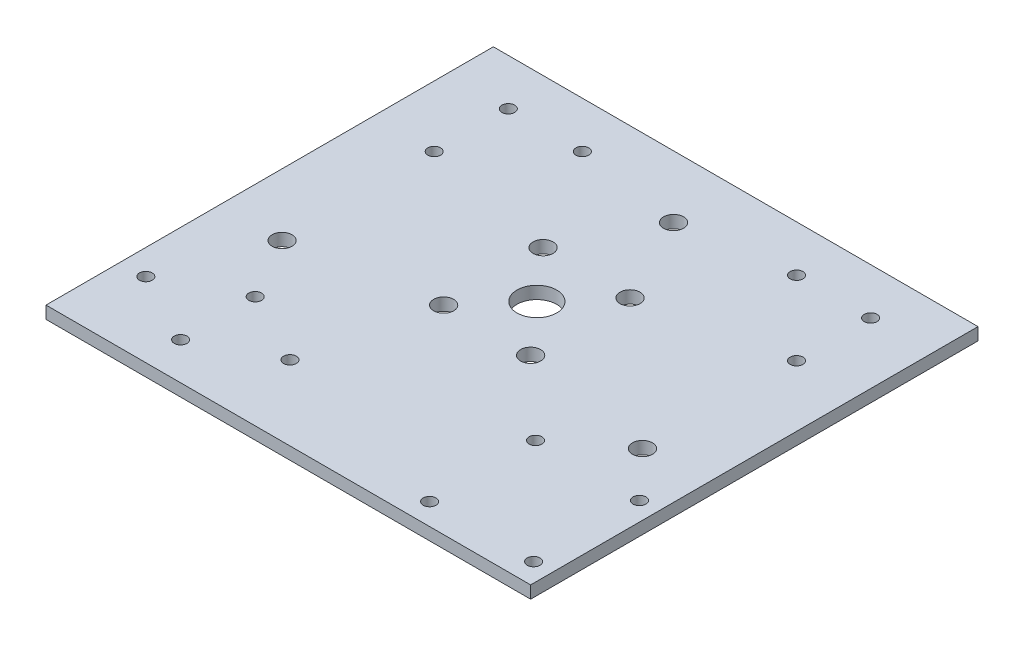
SolidWorks part; units mm, degrees
material "6061 Alloy"
ref_plane "Front Plane" through (0, 0, 0) normal (0, 0, 1) x (1, 0, 0)
ref_plane "Top Plane" through (0, 0, 0) normal (0, 1, 0) x (1, 0, 0)
ref_plane "Right Plane" through (0, 0, 0) normal (1, 0, 0) x (0, 0, -1)
sketch "Sketch1" plane through (0, 0, 0) normal (0, 1, 0) x (1, 0, 0)
  line L1 (-61.9125, -57.15) -> (61.9125, -57.15)
  line L2 (-61.9125, -57.15) -> (-61.9125, 57.15)
  line L3 (-61.9125, 57.15) -> (61.9125, 57.15)
  line L4 (61.9125, -57.15) -> (61.9125, 57.15)
  line L5 (-61.9125, -57.15) -> (61.9125, 57.15) construction
  line L6 (-61.9125, 57.15) -> (61.9125, -57.15) construction
  point P0 (0, 0)
  dimension "D1" = 114.3
  dimension "D2" = 123.825
extrude "Plate" add sketch "Sketch1" along normal blind 3.175 contours L1 L4 L3 L2
sketch "Sketch2" plane through (0, 3.175, 0) normal (0, 1, 0) x (1, 0, 0)
  circle A0 centre (0, 6.35) radius 5.08
  dimension "D1" = 10.16
  dimension "D2" = 6.35
extrude "Force Sensor Post Hole" cut sketch "Sketch2" against normal through all
hole_wizard "Gearbox Mount Holes (#4 clearance)" positions "Sketch9" profile "Sketch8" hole size "#4" standard "ANSI Inch" end condition up to next
sketch "Sketch9" plane through (0, 3.175, 0) normal (0, 1, 0) x (1, 0, 0)
  line L1 (-18.6309, -28.575) -> (-55.4609, -28.575) construction
  line L2 (-18.6309, -28.575) -> (-18.6309, -47.625) construction
  line L3 (-18.6309, -47.625) -> (-55.4609, -47.625) construction
  line L4 (-55.4609, -28.575) -> (-55.4609, -47.625) construction
  line L5 (-18.6309, -28.575) -> (-55.4609, -47.625) construction
  line L6 (-18.6309, -47.625) -> (-55.4609, -28.575) construction
  line L7 (-61.9125, -57.15) -> (-61.9125, 57.15) construction
  line L8 (-61.9125, -57.15) -> (61.9125, -57.15) construction
  point P0 (-55.4609, -38.1)
  point P3 (-37.0459, -28.575)
  point P6 (-18.6309, -38.1)
  point P9 (-37.0459, -47.625)
  dimension "D1" = 36.83
  dimension "D2" = 19.05
  dimension "D3" = 6.4516
  dimension "D4" = 9.525
sketch "Sketch8" plane through (-55.4609, 3.175, 38.1) normal (1, 0, 0) x (0, 0, 1)
  line L0 (0, 0) -> (0, 3.175)
  line L1 (0, 3.175) -> (1.6319, 3.175)
  line L2 (1.6319, 3.175) -> (1.6319, 0)
  line L5 (1.6319, 0) -> (0, 0)
  line L11 (0, -6.35) -> (0, 107.95) construction
  dimension "Thru Hole Dia." = 3.2639
  dimension "Thru Hole Depth" = 3.175
hole_wizard "Bearing Mount Holes (#4 clearance)" positions "Sketch12" profile "Sketch11" hole size "#4" standard "ANSI Inch"
sketch "Sketch12" plane through (0, 3.175, 0) normal (0, 1, 0) x (1, 0, 0)
  line L1 (30.5816, -51.6255) -> (57.15, -51.6255) construction
  line L2 (30.5816, -51.6255) -> (30.5816, -24.5745) construction
  line L3 (30.5816, -24.5745) -> (57.15, -24.5745) construction
  line L4 (57.15, -51.6255) -> (57.15, -24.5745) construction
  line L5 (30.5816, -51.6255) -> (57.15, -24.5745) construction
  line L6 (30.5816, -24.5745) -> (57.15, -51.6255) construction
  line L8 (-18.6309, -38.1) -> (30.5816, -38.1) construction
  point P3 (57.15, -24.5745)
  point P6 (30.5816, -51.6255)
  point P54 (30.5816, -24.5745)
  point P55 (57.15, -51.6255)
  dimension "D1" = 26.5684
  dimension "D2" = 27.051
  dimension "D3" = 49.2125
sketch "Sketch11" plane through (57.15, 3.175, 24.5745) normal (1, 0, 0) x (0, 0, 1)
  line L0 (0, 0) -> (0, 8.6006)
  line L1 (0, 8.6006) -> (1.6319, 7.62)
  line L2 (1.6319, 7.62) -> (1.6319, 0)
  line L5 (1.6319, 0) -> (0, 0)
  line L10 (0, 8.6006) -> (-1.632, 7.62) construction
  line L11 (0, -6.35) -> (0, 107.95) construction
  dimension "Hole Dia." = 3.2639
  dimension "Hole Depth" = 7.62
  dimension "Drill Angle" = 118
hole_wizard "Force Sensor Foundation Holes (#10 clearance)" positions "Sketch17" profile "Sketch16" hole size "#10" standard "ANSI Inch"
sketch "Sketch17" plane through (0, 3.175, 0) normal (0, 1, 0) x (1, 0, 0)
  line L1 (-11.1125, -6.35) -> (11.1125, -6.35) construction
  line L2 (-11.1125, -6.35) -> (-11.1125, 19.05) construction
  line L3 (-11.1125, 19.05) -> (11.1125, 19.05) construction
  line L4 (11.1125, -6.35) -> (11.1125, 19.05) construction
  line L5 (-11.1125, -6.35) -> (11.1125, 19.05) construction
  line L6 (-11.1125, 19.05) -> (11.1125, -6.35) construction
  point P24 (-11.1125, -6.35)
  point P25 (11.1125, 19.05)
  point P72 (-11.1125, 19.05)
  point P73 (11.1125, -6.35)
  point P81 (0, 6.35)
  dimension "D1" = 22.225
  dimension "D2" = 25.4
sketch "Sketch16" plane through (-11.1125, 3.175, 6.35) normal (1, 0, 0) x (0, 0, 1)
  line L0 (0, 0) -> (0, 9.1538)
  line L1 (0, 9.1538) -> (2.5527, 7.62)
  line L2 (2.5527, 7.62) -> (2.5527, 0)
  line L5 (2.5527, 0) -> (0, 0)
  line L10 (0, 9.1538) -> (-2.5527, 7.62) construction
  line L11 (0, -6.35) -> (0, 107.95) construction
  dimension "Hole Dia." = 5.1054
  dimension "Hole Depth" = 7.62
  dimension "Drill Angle" = 118
hole_wizard "Ball Caster Mount Holes (#4 clearance)" positions "Sketch19" profile "Sketch18" hole size "#4" standard "ANSI Inch" end condition up to next
sketch "Sketch19" plane through (0, 3.175, 0) normal (0, 1, 0) x (1, 0, 0)
  line L1 (-61.9125, 57.15) -> (-30.6705, 57.15) construction
  line L2 (-61.9125, 57.15) -> (-61.9125, 33.528) construction
  line L3 (-61.9125, 33.528) -> (-30.6705, 33.528) construction
  line L4 (-30.6705, 57.15) -> (-30.6705, 33.528) construction
  line L5 (-61.9125, 57.15) -> (-30.6705, 33.528) construction
  line L6 (-61.9125, 33.528) -> (-30.6705, 57.15) construction
  line L8 (-46.2915, 45.339) -> (-27.3685, 45.339) construction
  line L9 (-46.2915, 45.339) -> (-46.2915, 26.416) construction
  line L10 (-46.2915, 26.416) -> (-27.3685, 26.416) construction
  line L11 (-27.3685, 45.339) -> (-27.3685, 26.416) construction
  line L12 (-46.2915, 45.339) -> (-27.3685, 26.416) construction
  line L13 (-46.2915, 26.416) -> (-27.3685, 45.339) construction
  line L15 (61.9125, 57.15) -> (30.6705, 57.15) construction
  line L16 (61.9125, 57.15) -> (61.9125, 33.528) construction
  line L17 (61.9125, 33.528) -> (30.6705, 33.528) construction
  line L18 (30.6705, 57.15) -> (30.6705, 33.528) construction
  line L19 (61.9125, 57.15) -> (30.6705, 33.528) construction
  line L20 (61.9125, 33.528) -> (30.6705, 57.15) construction
  line L22 (46.2915, 45.339) -> (27.3685, 45.339) construction
  line L23 (46.2915, 45.339) -> (46.2915, 26.416) construction
  line L24 (46.2915, 26.416) -> (27.3685, 26.416) construction
  line L25 (27.3685, 45.339) -> (27.3685, 26.416) construction
  line L26 (46.2915, 45.339) -> (27.3685, 26.416) construction
  line L27 (46.2915, 26.416) -> (27.3685, 45.339) construction
  point P129 (-46.2915, 45.339)
  point P181 (-46.2915, 26.416)
  point P182 (-27.3685, 45.339)
  point P287 (46.2915, 45.339)
  point P377 (46.2915, 26.416)
  point P378 (27.3685, 45.339)
  dimension "D1" = 31.242
  dimension "D2" = 23.622
  dimension "D3" = 18.923
sketch "Sketch18" plane through (-46.2915, 3.175, -45.339) normal (1, 0, 0) x (0, 0, 1)
  line L0 (0, 0) -> (0, 3.175)
  line L1 (0, 3.175) -> (1.6319, 3.175)
  line L2 (1.6319, 3.175) -> (1.6319, 0)
  line L5 (1.6319, 0) -> (0, 0)
  line L11 (0, -6.35) -> (0, 107.95) construction
  dimension "Thru Hole Dia." = 3.2639
  dimension "Thru Hole Depth" = 3.175
hole_wizard "Top Plate Guide Holes (#10 clearance)" positions "Sketch21" profile "Sketch20" hole size "#10" standard "ANSI Inch" end condition up to next
sketch "Sketch21" plane through (0, 3.175, 0) normal (0, 1, 0) x (1, 0, 0)
  line L0 (-61.9125, 57.15) -> (61.9125, 57.15) construction
  line L1 (-61.9125, -57.15) -> (-61.9125, 57.15) construction
  line L2 (-61.9125, -57.15) -> (61.9125, -57.15) construction
  line L3 (61.9125, -57.15) -> (61.9125, 57.15) construction
  point P0 (-46.0375, -12.7)
  point P2 (46.0375, -12.7)
  point P4 (0, 41.275)
  dimension "D1" = 15.875
  dimension "D2" = 15.875
  dimension "D3" = 44.45
  dimension "D4" = 15.875
sketch "Sketch20" plane through (-46.0375, 3.175, 12.7) normal (1, 0, 0) x (0, 0, 1)
  line L0 (0, 0) -> (0, 3.175)
  line L1 (0, 3.175) -> (2.5527, 3.175)
  line L2 (2.5527, 3.175) -> (2.5527, 0)
  line L5 (2.5527, 0) -> (0, 0)
  line L11 (0, -6.35) -> (0, 107.95) construction
  dimension "Thru Hole Dia." = 5.1054
  dimension "Thru Hole Depth" = 3.175
